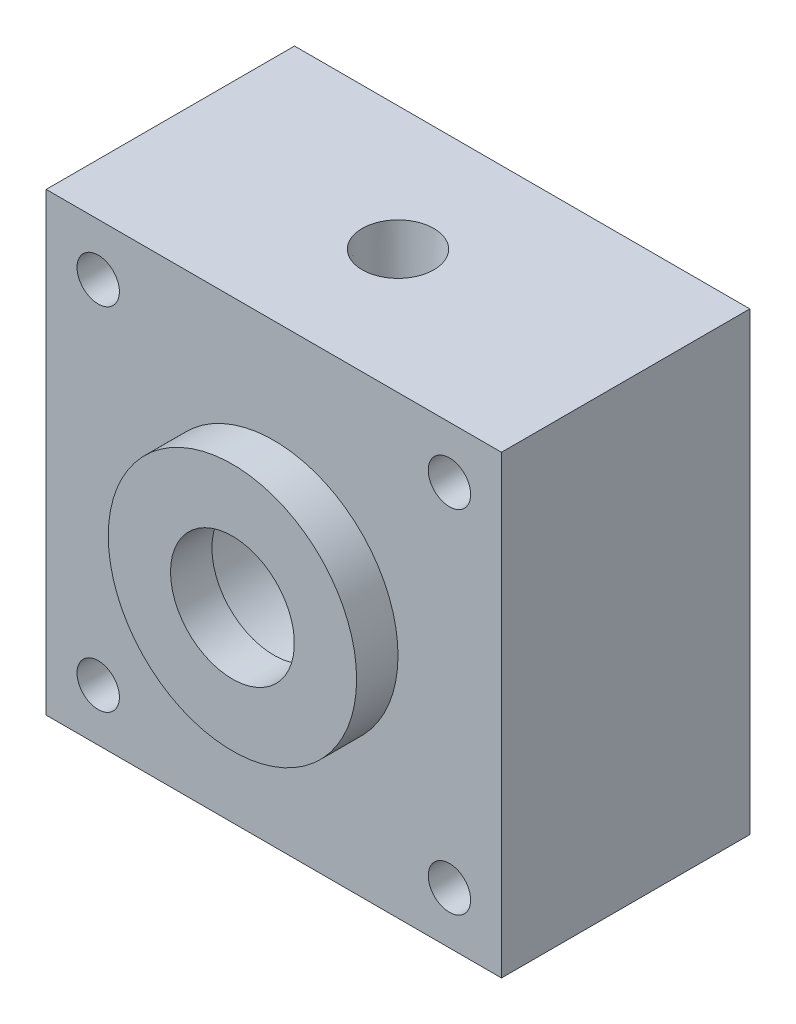
SolidWorks part; units mm, degrees
ref_plane "Front" through (0, 0, 0) normal (0, 0, 1) x (1, 0, 0)
ref_plane "Top" through (0, 0, 0) normal (0, 1, 0) x (1, 0, 0)
ref_plane "Right" through (0, 0, 0) normal (1, 0, 0) x (0, 0, -1)
sketch "Sketch1" plane through (0, 0, 0) normal (0, 0, 1) x (1, 0, 0)
  line L0 (-17.4625, 17.4625) -> (17.4625, 17.4625)
  line L1 (-17.4625, 17.4625) -> (-17.4625, -17.4625)
  line L2 (17.4625, -17.4625) -> (-17.4625, -17.4625)
  line L3 (17.4625, -17.4625) -> (17.4625, 17.4625)
  line L4 (17.4625, 17.4625) -> (-17.4625, -17.4625) construction
  dimension "D1" = 34.925
extrude "Base-Extrude" add sketch "Sketch1" along normal blind 19.05
sketch "Sketch12" plane through (-5.9785, 12.8213, 0) normal (0, 0, -1) x (-1, 0, 0)
  circle A0 centre (-5.9785, -12.8213) radius 14.25
  circle A1 centre (-5.9785, -12.8213) radius 15.875
  dimension "D1" = 28.5
  dimension "D2" = 31.75
extrude "Cut-Extrude4" cut sketch "Sketch12" against normal blind 1.524
sketch "Sketch3" plane through (0, 0, 19.05) normal (0, 0, 1) x (1, 0, 0)
  line L0 (0, 0) -> (17.4625, 17.4625) construction
  circle A0 centre (13.4704, 13.4704) radius 1.625
  circle A1 centre (0, 0) radius 19.05 construction
  dimension "D1" = 3.25
  dimension "D2" = 38.1
extrude "Cut-Extrude2" cut sketch "Sketch3" against normal through all
pattern_circular "CirPattern2" count 4 every 90 about axis through (0, 0, 0) along (0, 0, 1) of "Cut-Extrude2"
hole_wizard "Hole3" positions "Sketch9" profile "Sketch10" legacy
sketch "Sketch9" plane through (5.4711, 17.4625, 3.5795) normal (0, 1, 0) x (-1, 0, 0)
  line L1 (5.4711, 5.9455) -> (22.9336, 5.9455) construction
  line L3 (22.9336, 15.4705) -> (22.9336, -3.5795) construction
  line L4 (5.4711, -2.0555) -> (5.4711, -3.5795) construction
  point P0 (5.4711, 5.9455)
sketch "Sketch10" plane through (0, 17.4625, 9.525) normal (1, 0, 0) x (0, 0, 1)
  line L0 (0, 0) -> (0, 7.7999)
  line L1 (0, 7.7999) -> (2.413, 6.35)
  line L2 (2.413, 6.35) -> (2.413, 4.826)
  line L4 (2.7505, 0) -> (0, 0)
  line L5 (0, -4.0065) -> (0, 25.3083) construction
  line L6 (0, 7.7999) -> (-2.413, 6.35) construction
  line L7 (2.413, 4.826) -> (2.7505, 0)
  dimension "Depth" = 6.35
  dimension "Drill Angle" = 118
  dimension "Diameter" = 4.826
sketch "Sketch15" plane through (0, 0, 19.05) normal (0, 0, 1) x (1, 0, 0)
  circle A0 centre (0, 0) radius 9.525
  dimension "D1" = 19.05
extrude "Boss-Extrude1" add sketch "Sketch15" along normal blind 3.175
sketch "Sketch14" plane through (0, 0, 0) normal (0, 0, -1) x (-1, 0, 0)
  circle A0 centre (0, 0) radius 4.75
  dimension "D1" = 9.5
extrude "Cut-Extrude6" cut sketch "Sketch14" against normal through all
sketch "Sketch16" plane through (0, 0, 0) normal (0, 0, -1) x (-1, 0, 0)
  circle A0 centre (0, 0) radius 6.35
  dimension "D1" = 12.7
extrude "Cut-Extrude7" cut sketch "Sketch16" against normal up to surface (19.05 mm away)
sketch "Sketch17" plane through (0, 0, 0) normal (1, 0, 0) x (0, 0, -1)
  line L0 (-9.525, 11.1125) -> (-1.9489, -2.0097) construction
  line L1 (-9.525, 11.1125) -> (-9.525, 9.6626) construction
  line L2 (-9.525, 11.1125) -> (-10.5149, 10.541)
  line L3 (-11.938, 11.1125) -> (-7.112, 11.1125) construction
  line L4 (-10.5149, 10.541) -> (-4.0991, -0.5715)
  line L5 (-4.0991, -0.5715) -> (-3.1092, 0)
  line L6 (-3.1092, 0) -> (-9.525, 11.1125)
  line L7 (0, 0) -> (-24.9573, 0) construction
  line L8 (-22.225, 0) -> (-19.05, 0) construction
  dimension "D1" = 2.286
  dimension "D2" = 60
revolve "Cut-Revolve1" cut sketch "Sketch17" angle 360 about L0
